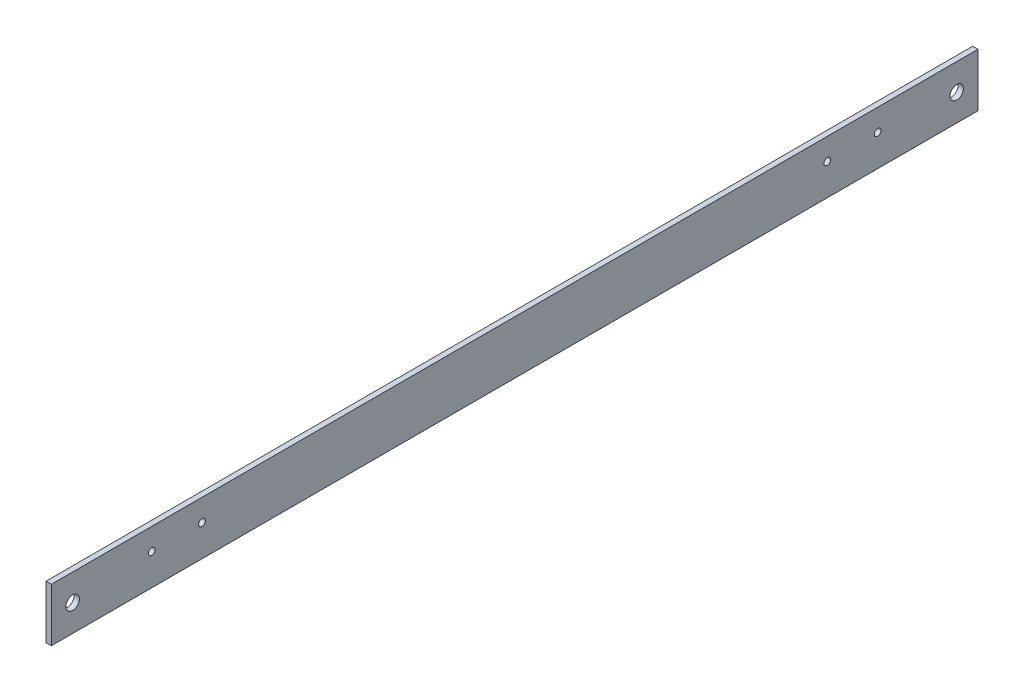
SolidWorks part; units mm, degrees
ref_plane "Front Plane" through (0, 0, 0) normal (0, 0, 1) x (1, 0, 0)
ref_plane "Top Plane" through (0, 0, 0) normal (0, 1, 0) x (1, 0, 0)
ref_plane "Right Plane" through (0, 0, 0) normal (1, 0, 0) x (0, 0, -1)
sketch "Sketch1" plane through (0, 0, 0) normal (1, 0, 0) x (0, 0, -1)
  line L1 (0, 0) -> (552.45, 0)
  line L2 (0, 0) -> (0, 31.75)
  line L3 (0, 31.75) -> (552.45, 31.75)
  line L4 (552.45, 0) -> (552.45, 31.75)
  circle A0 centre (12.7, 15.875) radius 4
  circle A1 centre (539.75, 15.875) radius 4
  circle A2 centre (462.625, 18.75) radius 2
  circle A3 centre (492.625, 18.75) radius 2
  circle A4 centre (59.825, 18.75) radius 2
  circle A5 centre (89.825, 18.75) radius 2
  dimension "D3" = 8
  dimension "D9" = 4
  dimension "D1" = 31.75
  dimension "D2" = 552.45
  dimension "D4" = 15.875
  dimension "D5" = 12.7
  dimension "D6" = 12.7
  dimension "D7" = 539.75
  dimension "D8" = 30
  dimension "D10" = 13
  dimension "D11" = 59.825
  dimension "D12" = 462.625
  dimension "D13" = 492.625
  dimension "D14" = 59.825
  dimension "D15" = 30
extrude "Boss-Extrude2" add sketch "Sketch1" along normal blind 3.175
equation "\"RailThickness\"= .125in'Spec"
equation "\"VSWidth\"= 1.25in'Spec"
equation "\"SideRailLength\"= 21.75in"
equation "\"StepperHolePadSize\"= \"StepperHoleDiameter\""
equation "\"D1@Sketch1\"=\"TopRailHeight\""
equation "\"D2@Sketch1\"=\"SideRailLength\""
equation "\"FrameFastenerHoleDiameter\"= 8mm"
equation "\"D3@Sketch1\"=\"FrameFastenerHoleDiameter\""
equation "\"D4@Sketch1\"=\"TopRailHeight\"/2"
equation "\"D5@Sketch1\"=\"FrameFastenerHoleOffsetFromEdge\""
equation "\"D6@Sketch1\"=\"FrameFastenerHoleOffsetFromEdge\""
equation "\"D1@Boss-Extrude2\"=\"RailThickness\""
equation "\"FrameFastenerHoleOffsetFromEdge\"= \"VSWidth\" / 2 - \"GapBetweenVerticalSupportsAndRails\" / 2"
equation "\"TopRailHeight\"= 1.25in"
equation "\"GapBetweenVerticalSupportsAndRails\"= \"RailThickness\" * 2"
equation "\"AngleBracketSmallHoleDiameter\"= 4mm"
equation "\"AngleBracketSlotDistanceBetweenHoles\"= 30mm"
equation "\"AngleBracketSlotDistanceFromTop\"= 13mm"
equation "\"D8@Sketch1\"=\"AngleBracketSlotDistanceBetweenHoles\""
equation "\"D9@Sketch1\"=\"AngleBracketSmallHoleDiameter\""
equation "\"D10@Sketch1\"=\"AngleBracketSlotDistanceFromTop\""
equation "\"AngleBracketSlotDistanceFromCorner\"= \"AngleBracketSlotDistanceFromBack\" - \"GapBetweenVerticalSupportsAndRails\" / 2'Equals 61.825"
equation "\"D11@Sketch1\"= \"AngleBracketSlotDistanceFromCorner\" - 2mm 'Minus 2mm to get screw hole in middle of slot"
equation "\"AngleBracketSlotDistanceFromBack\"= 65mm"
equation "\"D14@Sketch1\"= \"AngleBracketSlotDistanceFromCorner\" - 2mm'Minus 2mm to get screw hole in middle of slot"
equation "\"D15@Sketch1\"=\"AngleBracketSlotDistanceBetweenHoles\""
